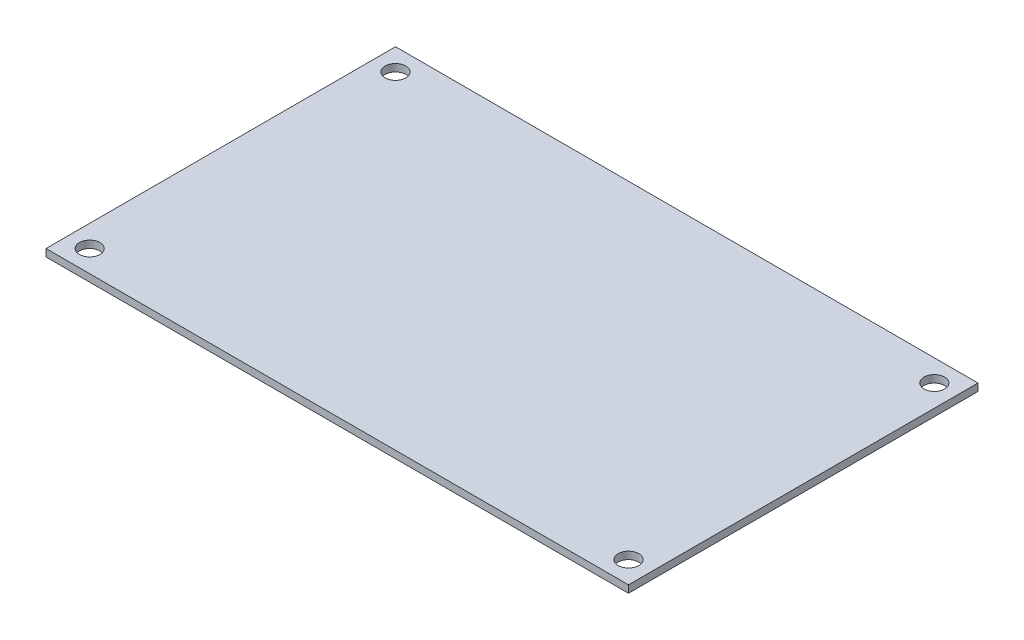
SolidWorks part; units mm, degrees
ref_plane "Front" through (0, 0, 0) normal (0, 0, 1) x (1, 0, 0)
ref_plane "Top" through (0, 0, 0) normal (0, 1, 0) x (1, 0, 0)
ref_plane "Right" through (0, 0, 0) normal (1, 0, 0) x (0, 0, -1)
sketch "Sketch1" plane through (0, 0, 0) normal (0, 1, 0) x (1, 0, 0)
  line L1 (-63.5, -38.1) -> (63.5, -38.1)
  line L2 (-63.5, -38.1) -> (-63.5, 38.1)
  line L3 (-63.5, 38.1) -> (63.5, 38.1)
  line L4 (63.5, -38.1) -> (63.5, 38.1)
  line L5 (-63.5, -38.1) -> (63.5, 38.1) construction
  line L6 (-63.5, 38.1) -> (63.5, -38.1) construction
  point P0 (0, 0)
  dimension "D1" = 127
  dimension "D2" = 76.2
extrude "Boss-Extrude1" add sketch "Sketch1" along normal blind 1.6
hole_wizard "M4 Clearance Hole1" positions "Sketch2" profile "Sketch3" hole size "M4" standard "ANSI Metric"
sketch "Sketch2" plane through (0, 1.6, 0) normal (0, 1, 0) x (1, 0, 0)
  line L1 (-58.7375, -33.3375) -> (58.7375, -33.3375)
  line L2 (-58.7375, -33.3375) -> (-58.7375, 33.3375)
  line L3 (-58.7375, 33.3375) -> (58.7375, 33.3375)
  line L4 (58.7375, -33.3375) -> (58.7375, 33.3375)
  line L5 (-58.7375, -33.3375) -> (58.7375, 33.3375) construction
  line L6 (-58.7375, 33.3375) -> (58.7375, -33.3375) construction
  line L7 (63.5, -38.1) -> (63.5, 38.1) construction
  line L8 (63.5, 38.1) -> (-63.5, 38.1) construction
  point P0 (-58.7375, 33.3375)
  point P2 (-58.7375, -33.3375)
  point P4 (58.7375, -33.3375)
  point P6 (58.7375, 33.3375)
  point P132 (63.5, 0)
  dimension "D1" = 4.7625
  dimension "D2" = 4.7625
sketch "Sketch3" plane through (-58.7375, 1.6, -33.3375) normal (1, 0, 0) x (0, 0, 1)
  line L0 (0, 0) -> (0, 51.3519)
  line L1 (0, 51.3519) -> (2.25, 50)
  line L2 (2.25, 50) -> (2.25, 0)
  line L5 (2.25, 0) -> (0, 0)
  line L10 (0, 51.3519) -> (-2.25, 50) construction
  line L11 (0, -6.35) -> (0, 107.95) construction
  dimension "Hole Dia." = 4.5
  dimension "Hole Depth" = 50
  dimension "Drill Angle" = 118
